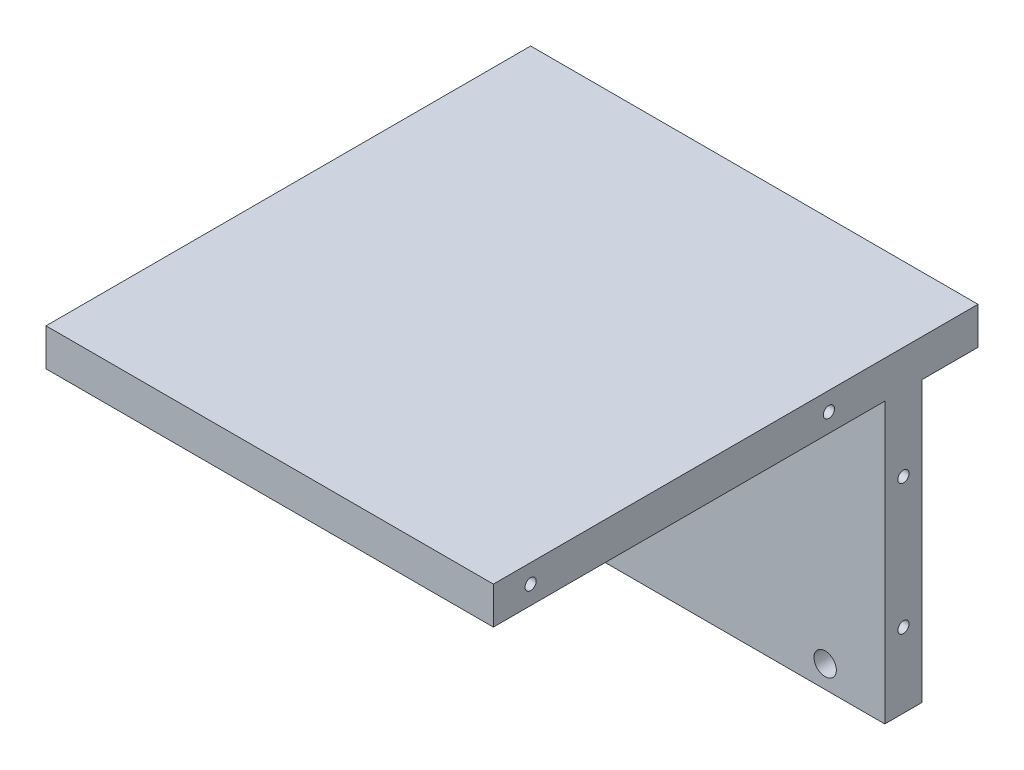
SolidWorks part; units mm, degrees
ref_plane "Front Plane" through (0, 0, 0) normal (0, 0, 1) x (1, 0, 0)
ref_plane "Top Plane" through (0, 0, 0) normal (0, 1, 0) x (1, 0, 0)
ref_plane "Right Plane" through (0, 0, 0) normal (1, 0, 0) x (0, 0, -1)
sketch "Sketch1" plane through (0, 0, 0) normal (0, 0, 1) x (1, 0, 0)
  line L1 (-60, 37.5) -> (60, 37.5)
  line L2 (-60, 37.5) -> (-60, -37.5)
  line L3 (-60, -37.5) -> (60, -37.5)
  line L4 (60, 37.5) -> (60, -37.5)
  line L5 (-60, 37.5) -> (60, -37.5) construction
  line L6 (-60, -37.5) -> (60, 37.5) construction
  circle A0 centre (-44, 31.5) radius 3
  circle A1 centre (44, 31.5) radius 3
  circle A2 centre (-44, -31.5) radius 3
  circle A3 centre (44, -31.5) radius 3
  point P0 (0, 0)
  dimension "D3" = 6
  dimension "D1" = 120
  dimension "D2" = 75
  dimension "D4" = 16
  dimension "D5" = 6
  dimension "D6" = 2
  dimension "D7" = 2
extrude "Boss-Extrude1" add sketch "Sketch1" along normal blind 10
sketch "Sketch2" plane through (0, 0, 10) normal (0, 0, 1) x (1, 0, 0)
  circle A0 centre (0, 10) radius 2.5
  circle A1 centre (0, -10) radius 2.5
  dimension "D1" = 5
  dimension "D2" = 10
  dimension "D3" = 2
extrude "Cut-Extrude1" cut sketch "Sketch2" against normal blind 7
sketch "Sketch3" plane through (60, 0, 0) normal (1, 0, 0) x (0, 0, -1)
  line L0 (-10, 37.5) -> (0, 37.5) construction
  line L1 (0, -37.5) -> (0, 37.5) construction
  circle A0 centre (-5, 17.5) radius 1.5
  circle A1 centre (-5, -17.5) radius 1.5
  dimension "D1" = 3
  dimension "D2" = 20
  dimension "D4" = 35
  dimension "D5" = 5
  dimension "D3" = 2
extrude "Cut-Extrude2" cut sketch "Sketch3" against normal blind 10
pattern_linear "LPattern1" count 2 spacing 110 along (-1, 0, 0) of "Cut-Extrude2"
sketch "Sketch4" plane through (0, 37.5, 0) normal (0, 1, 0) x (1, 0, 0)
  line L0 (60, 0) -> (-60, 0) construction
  line L1 (-60, 15) -> (60, 15)
  line L2 (-60, 15) -> (-60, -115)
  line L3 (-60, -115) -> (60, -115)
  line L4 (60, 15) -> (60, -115)
  line L5 (60, -10) -> (60, 0) construction
  line L6 (-60, -10) -> (-60, 0) construction
  dimension "D1" = 130
  dimension "D2" = 15
extrude "Boss-Extrude2" add sketch "Sketch4" along normal blind 10
sketch "Sketch5" plane through (60, 0, 0) normal (1, 0, 0) x (0, 0, -1)
  line L0 (-115, 37.5) -> (-10, 37.5) construction
  line L1 (-115, 47.5) -> (-115, 37.5) construction
  circle A0 centre (-105, 42.5) radius 1.5
  circle A1 centre (-25, 42.5) radius 1.5
  dimension "D1" = 3
  dimension "D2" = 5
  dimension "D3" = 10
  dimension "D5" = 80
  dimension "D4" = 2
extrude "Cut-Extrude3" cut sketch "Sketch5" against normal blind 10
pattern_linear "LPattern2" count 2 spacing 110 along (-1, 0, 0) of "Cut-Extrude3"
